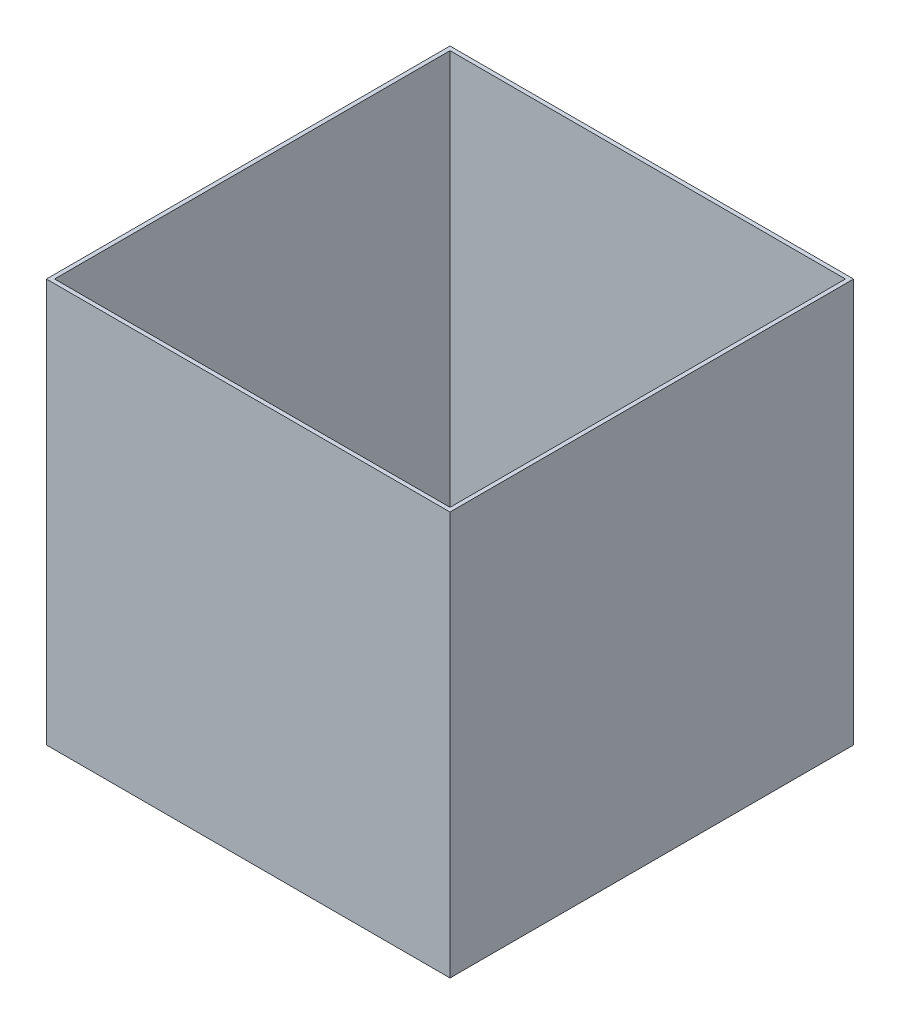
SolidWorks part; units mm, degrees
ref_plane "Front Plane" through (0, 0, 0) normal (0, 0, 1) x (1, 0, 0)
ref_plane "Top Plane" through (0, 0, 0) normal (0, 1, 0) x (1, 0, 0)
ref_plane "Right Plane" through (0, 0, 0) normal (1, 0, 0) x (0, 0, -1)
sketch "Sketch1" plane through (0, 0, 0) normal (0, 1, 0) x (1, 0, 0)
  line L1 (-25, 25) -> (25, 25)
  line L2 (-25, 25) -> (-25, -25)
  line L3 (-25, -25) -> (25, -25)
  line L4 (25, 25) -> (25, -25)
  line L5 (-25, 25) -> (25, -25) construction
  line L6 (-25, -25) -> (25, 25) construction
  point P0 (0, 0)
  dimension "D1" = 50
  dimension "D2" = 50
extrude "Boss-Extrude1" add sketch "Sketch1" along normal blind 50
shell "Shell1" thickness 0.5
